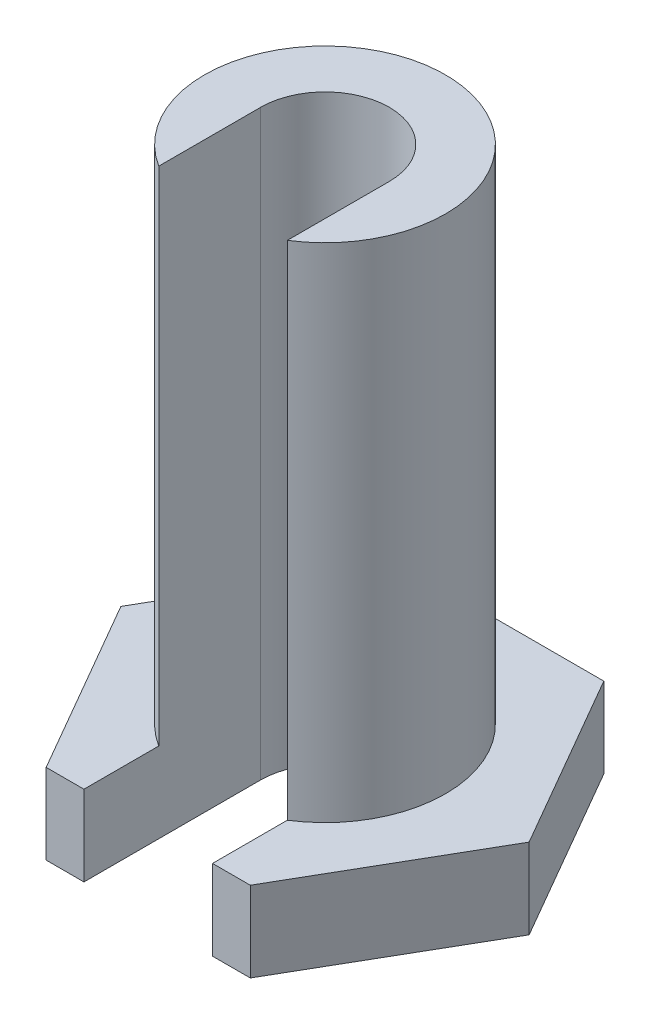
SolidWorks part; units mm, degrees
ref_plane "Front Plane" through (0, 0, 0) normal (0, 0, 1) x (1, 0, 0)
ref_plane "Top Plane" through (0, 0, 0) normal (0, 1, 0) x (1, 0, 0)
ref_plane "Right Plane" through (0, 0, 0) normal (1, 0, 0) x (0, 0, -1)
sketch "Sketch1" plane through (0, 0, 0) normal (0, 1, 0) x (1, 0, 0)
  circle A0 centre (0, 0) radius 3
  dimension "D1" = 6
extrude "Boss-Extrude1" add sketch "Sketch1" along normal blind 14.5
sketch "Sketch3" plane through (0, 0, 0) normal (0, -1, 0) x (-1, 0, 0)
  line L1 (5.0807, 0) -> (2.5403, 4.4)
  line L2 (2.5403, 4.4) -> (-2.5403, 4.4)
  line L3 (-2.5403, 4.4) -> (-5.0807, 0)
  line L4 (-5.0807, 0) -> (-2.5403, -4.4)
  line L5 (-2.5403, -4.4) -> (2.5403, -4.4)
  line L6 (2.5403, -4.4) -> (5.0807, 0)
  circle A0 centre (0, 0) radius 4.4 construction
  dimension "D1" = 4.4
extrude "Boss-Extrude2" add sketch "Sketch3" against normal blind 2
sketch "Sketch4" plane through (0, 14.5, 0) normal (0, 1, 0) x (1, 0, 0)
  line L0 (-1.6, 0) -> (-1.6, -4.4)
  line L1 (2.5403, -4.4) -> (-2.5403, -4.4) construction
  line L2 (-1.6, -4.4) -> (1.6, -4.4)
  line L3 (1.6, -4.4) -> (1.6, 0)
  arc A0 (1.6, 0) -> (-1.6, 0) centre (0, 0) ccw
  dimension "D1" = 3.2
extrude "Cut-Extrude1" cut sketch "Sketch4" against normal through all both and the other way through all
